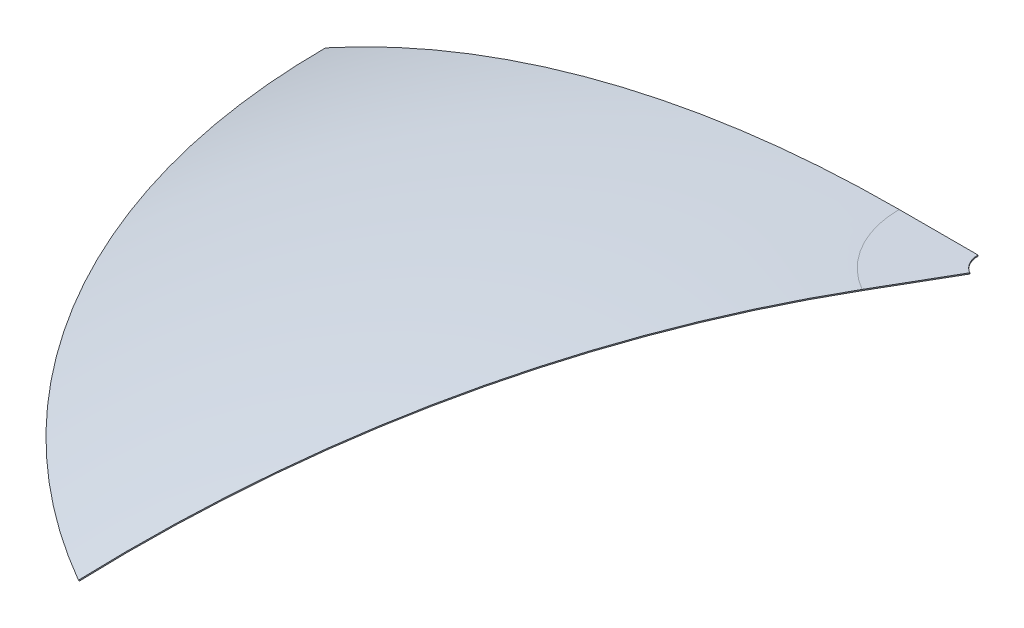
SolidWorks part; units mm, degrees
ref_plane "Front Plane" through (0, 0, 0) normal (0, 0, 1) x (1, 0, 0)
ref_plane "Top Plane" through (0, 0, 0) normal (0, 1, 0) x (1, 0, 0)
ref_plane "Right Plane" through (0, 0, 0) normal (1, 0, 0) x (0, 0, -1)
sketch "Sketch1" plane through (0, 0, 0) normal (0, 0, 1) x (1, 0, 0)
  line L0 (45, 1.5) -> (-45, 1.5) construction
  line L1 (45, 1.5) -> (-45, 1.5) construction
  line L2 (10, 1.5) -> (-10, 1.5) construction
  line L3 (10, 1.5) -> (-10, 1.5) construction
  line L4 (-45, 1.5) -> (-10, 1.5)
  line L6 (-45, 2) -> (-10, 2)
  line L7 (-10, 2) -> (-10, 1.5)
  line L8 (-299.7402, -63.211) -> (-299.5, -63.6495)
  line L9 (0, -998.5) -> (0, 49001.5) construction
  arc A0 (-46.0019, 1.4991) -> (-299.5, -63.6495) centre (-45, -528.1639) ccw construction
  arc A1 (-46.0019, 1.4991) -> (-299.5, -63.6495) centre (-45, -528.1639) ccw
  arc A2 (-45, 1.5) -> (-46.0019, 1.4991) centre (-45, -528.1639) ccw
  arc A3 (-46.0028, 1.9991) -> (-299.7402, -63.211) centre (-45, -528.1639) ccw
  arc A4 (-45, 2) -> (-46.0028, 1.9991) centre (-45, -528.1639) ccw
  point P17 (0, 1.5)
  dimension "D1" = 0.5
revolve "Revolve1" add sketch "Sketch1" angle 60 about L9
sketch "Sketch3" plane through (0, 2, 0) normal (0, 1, 0) x (1, 0, 0)
  line L0 (-10, 0) -> (-5, -8.6603)
  arc A0 (-10, 0) -> (-5, -8.6603) centre (0, 0) ccw construction
  arc A1 (-10, 0) -> (-5, -8.6603) centre (0, 0) ccw
extrude "Boss-Extrude1" [suppressed] add sketch "Sketch3" against normal up to surface (0.5 mm away)
